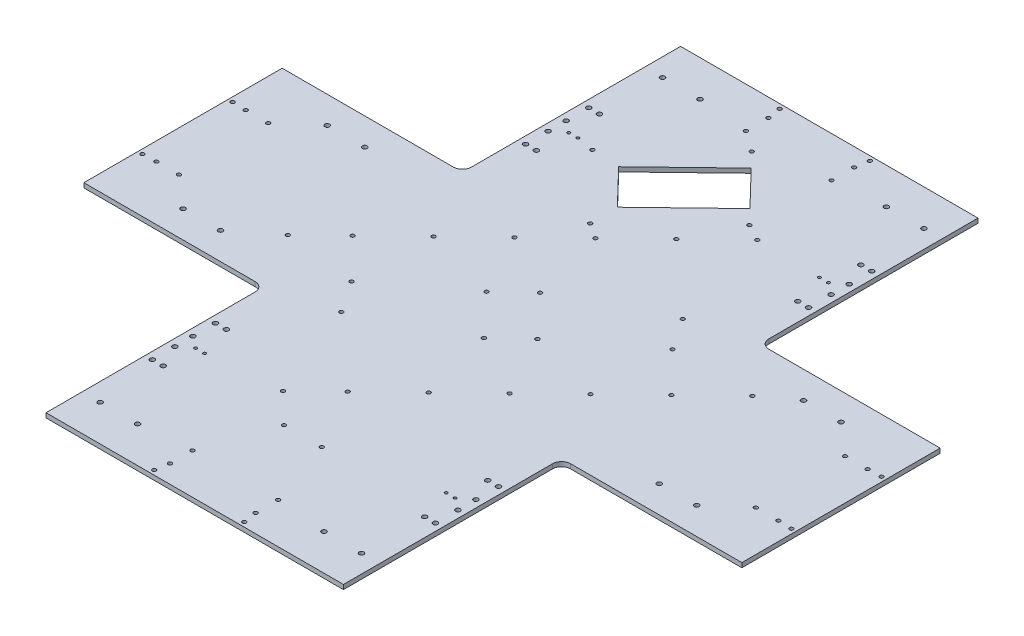
SolidWorks part; units mm, degrees
other "Markup1"
sketch "Sketch8"
material "3.0205 (EN-AW 1200)"
ref_plane "前视基准面" through (0, 0, 0) normal (0, 0, 1) x (1, 0, 0)
ref_plane "上视基准面" through (0, 0, 0) normal (0, 1, 0) x (1, 0, 0)
ref_plane "右视基准面" through (0, 0, 0) normal (1, 0, 0) x (0, 0, -1)
other "Configuration Table"
sketch "Sketch1" plane through (0, 0, 0) normal (0, 1, 0) x (1, 0, 0)
  line L0 (165, 352) -> (-165, 352)
  line L1 (-165, 352) -> (-165, 110)
  line L2 (-165, 110) -> (-365, 110)
  line L5 (-365, 110) -> (-365, -110)
  line L6 (0, 352) -> (0, -66.8675) construction
  line L7 (-365, 0) -> (131.0517, 0) construction
  line L8 (365, 110) -> (365, -110)
  line L11 (165, 110) -> (365, 110)
  line L12 (165, 352) -> (165, 110)
  line L13 (165, -352) -> (165, -110)
  line L14 (165, -110) -> (365, -110)
  line L19 (-165, -110) -> (-365, -110)
  line L20 (-165, -352) -> (-165, -110)
  line L21 (165, -352) -> (-165, -352)
  point P21 (365, 0)
  dimension "D1" = 165
  dimension "D2" = 200
  dimension "D3" = 110
  dimension "D4" = 242
extrude "Boss-Extrude1" add sketch "Sketch1" along normal blind 5
sketch "Sketch2" plane through (0, 5, 0) normal (0, 1, 0) x (1, 0, 0)
  line L3 (365, -110) -> (365, 110) construction
  line L4 (-56.7455, 0) -> (47.5165, 0) construction
  line L5 (0, 54.7142) -> (0, -64.2255) construction
  line L7 (165, 352) -> (-165, 352) construction
  circle A0 centre (345, 49.5) radius 2.125
  circle A1 centre (320, 49.5) radius 2.125
  circle A7 centre (320, -49.5) radius 2.125
  circle A8 centre (345, -49.5) radius 2.125
  circle A9 centre (-345, -49.5) radius 2.125
  circle A10 centre (-320, -49.5) radius 2.125
  circle A13 centre (-320, 49.5) radius 2.125
  circle A14 centre (-345, 49.5) radius 2.125
  circle A15 centre (47.5, 332) radius 2.125
  circle A16 centre (47.5, 307) radius 2.125
  circle A17 centre (-47.5, 307) radius 2.125
  circle A18 centre (-47.5, 332) radius 2.125
  circle A19 centre (-47.5, -332) radius 2.125
  circle A20 centre (-47.5, -307) radius 2.125
  circle A21 centre (47.5, -307) radius 2.125
  circle A22 centre (47.5, -332) radius 2.125
  dimension "D3" = 49.5
  dimension "D5" = 4.25
  dimension "D7" = 4.25
  dimension "D9" = 4.25
  dimension "D10" = 4.25
  dimension "D2" = 47.5
  dimension "D4" = 25
  dimension "D6" = 20
  dimension "20" = 20
  dimension "D13" = 25
extrude "Cut-Extrude1" cut sketch "Sketch2" against normal blind 3
sketch "Sketch4" plane through (0, 5, 0) normal (0, 1, 0) x (1, 0, 0)
  line L0 (-165, 352) -> (-165, 110) construction
  line L1 (165, 352) -> (-165, 352) construction
  line L2 (0, 46.9886) -> (0, -40.2904) construction
  line L3 (-35.103, 0) -> (92.4951, 0) construction
  line L5 (165, -352) -> (165, -110) construction
  circle A0 centre (-157, 172) radius 2.6
  circle A1 centre (-145, 172) radius 2.6
  circle A2 centre (-157, 197) radius 2.6
  circle A3 centre (-157, 217) radius 2.6
  circle A4 centre (-157, 242) radius 2.6
  circle A5 centre (-145, 242) radius 2.6
  circle A6 centre (145, 242) radius 2.6
  circle A7 centre (157, 242) radius 2.6
  circle A8 centre (157, 217) radius 2.6
  circle A9 centre (157, 197) radius 2.6
  circle A10 centre (145, 172) radius 2.6
  circle A11 centre (157, 172) radius 2.6
  circle A12 centre (157, -172) radius 2.6
  circle A13 centre (145, -172) radius 2.6
  circle A14 centre (157, -197) radius 2.6
  circle A15 centre (157, -217) radius 2.6
  circle A16 centre (157, -242) radius 2.6
  circle A17 centre (145, -242) radius 2.6
  circle A18 centre (-145, -242) radius 2.6
  circle A19 centre (-157, -242) radius 2.6
  circle A20 centre (-157, -217) radius 2.6
  circle A21 centre (-157, -197) radius 2.6
  circle A22 centre (-145, -172) radius 2.6
  circle A23 centre (-157, -172) radius 2.6
  circle A24 centre (144, -207) radius 1.6
  circle A25 centre (-144, -207) radius 1.6
  circle A26 centre (144, 207) radius 1.6
  circle A27 centre (-144, 207) radius 1.6
  circle A28 centre (134, -207) radius 1.6
  circle A29 centre (-134, -207) radius 1.6
  circle A30 centre (134, 207) radius 1.6
  circle A31 centre (-134, 207) radius 1.6
  dimension "D3" = 5.2
  dimension "D4" = 5.2
  dimension "D5" = 8
  dimension "D6" = 8
  dimension "D9" = 5.2
  dimension "D10" = 5.2
  dimension "D11" = 5.2
  dimension "D12" = 5.2
  dimension "D19" = 3.2
  dimension "D20" = 21
  dimension "D21" = 10
  dimension "D22" = 3.2
  dimension "D23" = 10
  dimension "D1" = 8
  dimension "D2" = 20
  dimension "D7" = 8
  dimension "D8" = 20
  dimension "D13" = 25
  dimension "D14" = 20
  dimension "D15" = 25
  dimension "D16" = 25
  dimension "D17" = 110
  dimension "D18" = 0
extrude "Cut-Extrude3" cut sketch "Sketch4" against normal blind 10
sketch "Sketch5" plane through (0, 5, 0) normal (0, 1, 0) x (1, 0, 0)
  line L0 (165, 352) -> (-165, 352) construction
  line L5 (-46.9195, 0) -> (66.6223, 0) construction
  line L6 (0, 59.0569) -> (0, -54.4849) construction
  line L10 (-365, 110) -> (-365, -110) construction
  circle A0 centre (-50, 347) radius 2.125
  circle A1 centre (50, 347) radius 2.125
  circle A2 centre (50, -347) radius 2.125
  circle A3 centre (-50, -347) radius 2.125
  circle A4 centre (-360, 50) radius 2.125
  circle A5 centre (-360, -50) radius 2.125
  circle A6 centre (360, -50) radius 2.125
  circle A7 centre (360, 50) radius 2.125
  dimension "D1" = 4.25
  dimension "D2" = 4.25
  dimension "D3" = 50
  dimension "D6" = 4.25
  dimension "D7" = 4.25
  dimension "5" = 5
  dimension "D4" = 50
  dimension "D5" = 50
  dimension "D8" = 50
  dimension "D9" = 5
  dimension "D10" = 5
extrude "Cut-Extrude4" cut sketch "Sketch5" against normal blind 10
fillet "Fillet1" radius 10 4 edges at (-165, 2.5, -110) (-165, 2.5, 110) (165, 2.5, 110) (165, 2.5, -110)
sketch "Sketch6" plane through (0, 5, 0) normal (0, 1, 0) x (1, 0, 0)
  line L0 (165, 352) -> (-165, 352) construction
  line L1 (-165, 352) -> (-165, 120) construction
  line L3 (0, 50.3702) -> (0, -42.7646) construction
  line L4 (-54.8568, 0) -> (91.2004, 0) construction
  line L5 (365, 110) -> (175, 110) construction
  line L6 (365, -110) -> (365, 110) construction
  circle A0 centre (-145, 312) radius 2.6
  circle A1 centre (-103.4, 312) radius 2.6
  circle A4 centre (103.4, 312) radius 2.6
  circle A5 centre (145, 312) radius 2.6
  circle A6 centre (145, -312) radius 2.6
  circle A7 centre (103.4, -312) radius 2.6
  circle A8 centre (-103.4, -312) radius 2.6
  circle A9 centre (-145, -312) radius 2.6
  circle A10 centre (243.4, 80) radius 2.6
  circle A11 centre (285, 80) radius 2.6
  circle A12 centre (285, -80) radius 2.6
  circle A13 centre (243.4, -80) radius 2.6
  circle A14 centre (-243.4, -80) radius 2.6
  circle A15 centre (-285, -80) radius 2.6
  circle A16 centre (-285, 80) radius 2.6
  circle A17 centre (-243.4, 80) radius 2.6
  dimension "D1" = 5.2
  dimension "D2" = 5.2
  dimension "D3" = 5.2
  dimension "D4" = 5.2
  dimension "D5" = 40
  dimension "D8" = 30
  dimension "D6" = 20
  dimension "D7" = 41.6
  dimension "D9" = 80
  dimension "D10" = 41.6
extrude "Cut-Extrude5" cut sketch "Sketch6" against normal blind 10
sketch "Sketch7" plane through (0, 5, 0) normal (0, 1, 0) x (1, 0, 0)
  line L0 (168.2678, 162.2747) -> (-147.1807, -141.9387) construction
  line L1 (165, 306.3846) -> (-266.7624, -110) construction
  line L2 (165, 120) -> (165, 352) construction
  line L3 (-365, -110) -> (-175, -110) construction
  line L4 (266.7624, 110) -> (-165, -306.3846) construction
  line L5 (365, 110) -> (175, 110) construction
  line L6 (-165, -120) -> (-165, -352) construction
  line L7 (-262.1332, -51.5521) -> (-40.7959, -281.0637) construction
  line L8 (86.9657, 260.9852) -> (334.6169, 4.1878) construction
  line L9 (-73.5822, 76.2998) -> (73.5822, -76.2998) construction
  line L11 (-365, -352) -> (365, -352) construction
  line L12 (-365, -352) -> (-365, 352) construction
  line L13 (-365, 352) -> (365, 352) construction
  line L14 (365, -352) -> (365, 352) construction
  line L15 (-365, -352) -> (365, 352) construction
  line L16 (-365, 352) -> (365, -352) construction
  circle A4 centre (-73.5822, 76.2998) radius 2.125
  circle A5 centre (-27.8744, 120.3797) radius 2.125
  circle A6 centre (17.8335, 164.4596) radius 2.125
  circle A7 centre (63.5414, 208.5395) radius 2.125
  circle A8 centre (-119.2901, 32.2198) radius 2.125
  circle A9 centre (-164.998, -11.8601) radius 2.125
  circle A10 centre (-201.5643, -47.124) radius 2.125
  circle A11 centre (-54.3998, -199.7236) radius 2.125
  circle A12 centre (-17.8335, -164.4596) radius 2.125
  circle A13 centre (27.8744, -120.3797) radius 2.125
  circle A14 centre (210.7059, 55.94) radius 2.125
  circle A15 centre (164.998, 11.8601) radius 2.125
  circle A16 centre (119.2901, -32.2198) radius 2.125
  circle A17 centre (73.5822, -76.2998) radius 2.125
  point P53 (0, 0)
  dimension "D6" = 4.25
  dimension "D7" = 4.25
  dimension "D8" = 4.25
  dimension "D9" = 4.25
  dimension "D10" = 4.25
  dimension "D11" = 4.25
  dimension "D12" = 4.25
  dimension "D1" = 106
  dimension "D2" = 730
  dimension "D3" = 20
  dimension "D4" = 20
  dimension "D5" = 0
  dimension "D13" = 63.5
  dimension "D14" = 63.5
  dimension "D15" = 50.8
  dimension "D16" = 63.5
  dimension "D17" = 63.5
  dimension "D18" = 63.5
  dimension "D19" = 704
extrude "Cut-Extrude6" cut sketch "Sketch7" against normal blind 10
sketch "Sketch9" plane through (0, 5, 0) normal (0, 1, 0) x (1, 0, 0)
  line L0 (167.9289, 112.9289) -> (-167.9289, -112.9289) construction
  line L1 (80.349, 117.7232) -> (149.9169, 14.2734) construction
  line L2 (-142.2885, -25.6171) -> (-87.1446, -107.6179) construction
  line L3 (0, 45.0584) -> (0, -52.9183) construction
  line L4 (-44.6513, 0) -> (48.0404, 0) construction
  line L5 (165, 352) -> (-165, 352) construction
  arc A0 (165, 120) -> (175, 110) centre (175, 120) ccw construction
  arc A1 (-165, -120) -> (-175, -110) centre (-175, -120) ccw construction
  circle A2 centre (-121.5605, -56.4403) radius 2.1
  circle A3 centre (-98.123, -91.2926) radius 2.1
  circle A4 centre (98.123, 91.2926) radius 2.1
  circle A5 centre (121.5605, 56.4403) radius 2.1
  circle A7 centre (21, 232) radius 2.1
  circle A8 centre (-21, 232) radius 2.1
  circle A9 centre (-21, -232) radius 2.1
  circle A10 centre (21, -232) radius 2.1
  dimension "D3" = 4.2
  dimension "D4" = 4.2
  dimension "D5" = 4.2
  dimension "D6" = 4.2
  dimension "D11" = 120
  dimension "D12" = 4.2
  dimension "D1" = 70
  dimension "D2" = 70
  dimension "D7" = 21
  dimension "D8" = 21
  dimension "D9" = 21
  dimension "D10" = 21
  dimension "D13" = 21
extrude "Cut-Extrude7" cut sketch "Sketch9" against normal blind 10
sketch "Sketch10" plane through (0, 5, 0) normal (0, 1, 0) x (1, 0, 0)
  line L0 (67.9147, 240.5422) -> (-129.908, 49.7653) construction
  line L5 (-8.4462, 305.8268) -> (-216.5396, 105.1449) construction
  line L6 (63.5414, 208.5395) -> (-73.5822, 76.2998) construction
  line L7 (44.9761, 218.4207) -> (-24.4411, 290.4016) construction
  line L8 (-45, 131.6492) -> (-114.4172, 203.6301) construction
  line L9 (165, 120) -> (165, 352) construction
  line L10 (-115.0505, 133.5564) -> (29.5947, 273.0499) construction
  line L11 (-8.8222, 274.2059) -> (29.3573, 234.6164)
  line L12 (29.3573, 234.6164) -> (-45.5029, 162.4225)
  line L13 (-45.5029, 162.4225) -> (-83.6823, 202.012)
  line L14 (-83.6823, 202.012) -> (-8.8222, 274.2059)
  circle A0 centre (44.9761, 218.4207) radius 2.125
  circle A1 centre (-45, 131.6492) radius 2.125
  circle A3 centre (-114.4172, 203.6301) radius 2.125
  circle A4 centre (-24.4411, 290.4016) radius 2.125
  dimension "D3" = 4.25
  dimension "D4" = 4.25
  dimension "D7" = 4.25
  dimension "D8" = 4.25
  dimension "D1" = 20
  dimension "D2" = 100
  dimension "D5" = 210
  dimension "D6" = 125
  dimension "D9" = 50
  dimension "D10" = 55
  dimension "D11" = 27.5
  dimension "D12" = 104
extrude "Cut-Extrude8" cut sketch "Sketch10" against normal blind 10
sketch "Sketch11" plane through (0, 5, 0) normal (0, 1, 0) x (1, 0, 0)
  line L0 (6.1878, -37.3492) -> (36.8561, -8.6533) construction
  line L1 (-36.8561, 8.6533) -> (-6.1878, 37.3492) construction
  line L2 (-6.1878, 37.3492) -> (36.8561, -8.6533) construction
  line L7 (6.1878, -37.3492) -> (-36.8561, 8.6533) construction
  line L9 (-15.3342, -14.348) -> (15.3342, 14.348) construction
  line L10 (-21.5219, 23.0012) -> (21.5219, -23.0012) construction
  circle A0 centre (-6.1878, 37.3492) radius 2.15
  circle A1 centre (36.8561, -8.6533) radius 2.15
  circle A2 centre (6.1878, -37.3492) radius 2.15
  circle A3 centre (-36.8561, 8.6533) radius 2.15
  point P10 (0, 0)
  point P14 (0, 0)
  dimension "D5" = 42
  dimension "D6" = 63
  dimension "D7" = 4.3
extrude "Cut-Extrude9" cut sketch "Sketch11" against normal blind 10
